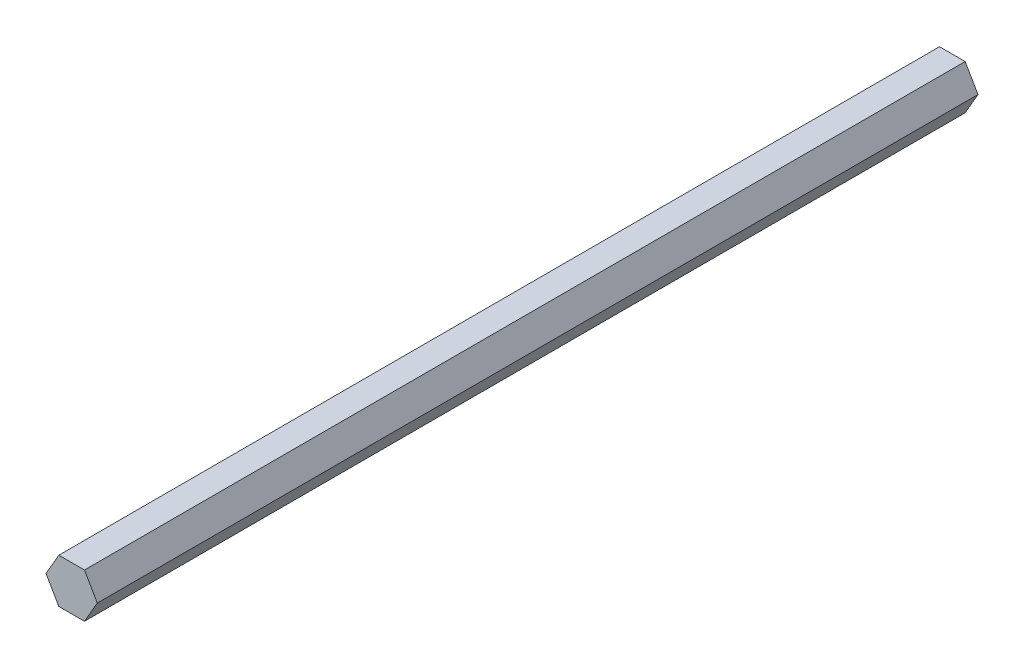
SolidWorks part; units mm, degrees
other "Axis2"
material "Alloy Steel"
ref_plane "Front" through (0, 0, 0) normal (0, 0, 1) x (1, 0, 0)
ref_plane "Top" through (0, 0, 0) normal (0, 1, 0) x (1, 0, 0)
ref_plane "Right" through (0, 0, 0) normal (1, 0, 0) x (0, 0, -1)
sketch "AxisSke" plane through (0, 0, 0) normal (0, 0, 1) x (1, 0, 0)
  line L1 (0.9988, 0) -> (0.4994, 0.865)
  line L2 (0.4994, 0.865) -> (-0.4994, 0.865)
  line L3 (-0.4994, 0.865) -> (-0.9988, 0)
  line L4 (-0.9988, 0) -> (-0.4994, -0.865)
  line L5 (-0.4994, -0.865) -> (0.4994, -0.865)
  line L6 (0.4994, -0.865) -> (0.9988, 0)
  circle A0 centre (0, 0) radius 0.865 construction
  dimension "D1" = 1.73
extrude "Axis" add sketch "AxisSke" along normal blind 34.3
